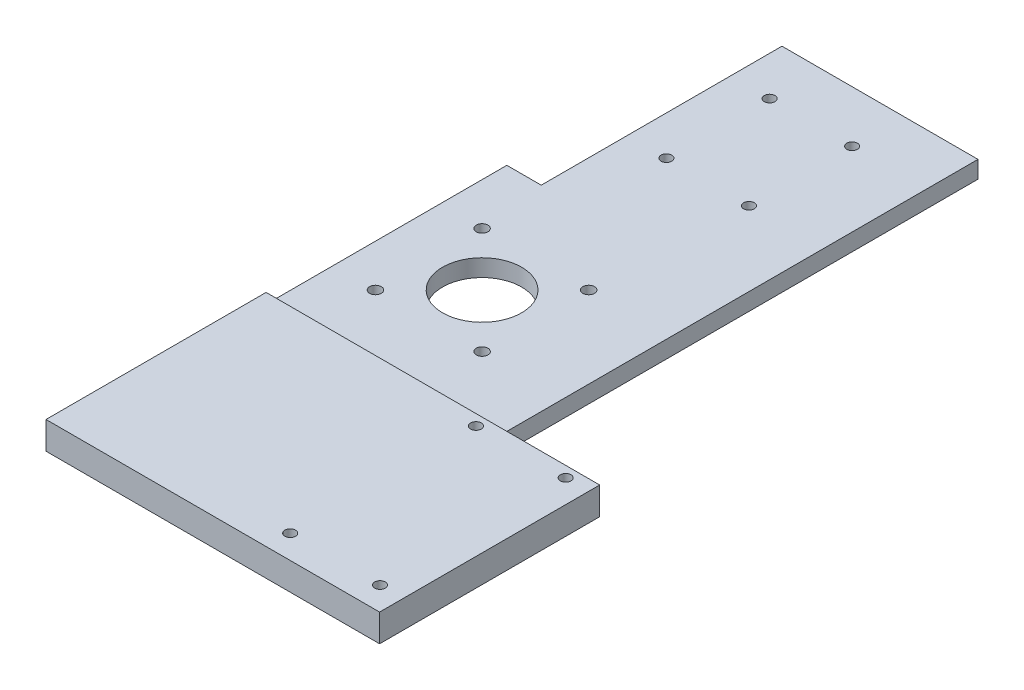
SolidWorks part; units mm, degrees
ref_plane "前视基准面" through (0, 0, 0) normal (0, 0, 1) x (1, 0, 0)
ref_plane "上视基准面" through (0, 0, 0) normal (0, 1, 0) x (1, 0, 0)
ref_plane "右视基准面" through (0, 0, 0) normal (1, 0, 0) x (0, 0, -1)
other "Configuration Table"
sketch "草图1" plane through (0, 0, 0) normal (0, 1, 0) x (1, 0, 0)
  line L1 (0, 0) -> (57, 0)
  line L2 (0, 0) -> (0, -140)
  line L3 (0, -140) -> (57, -140)
  line L4 (57, 0) -> (57, -140)
  dimension "D1" = 57
  dimension "D2" = 140
extrude "凸台-拉伸1" add sketch "草图1" along normal blind 5
sketch "草图2" plane through (0, 0, 0) normal (0, -1, 0) x (1, 0, 0)
  circle A0 centre (11.4, 45) radius 1.55 construction
  circle A1 centre (11.4, 15) radius 1.55 construction
  circle A2 centre (35.4, 15) radius 1.55 construction
  circle A3 centre (35.4, 45) radius 1.55 construction
  circle A4 centre (11.4, 45) radius 1.55
  circle A5 centre (11.4, 15) radius 1.55
  circle A6 centre (35.4, 15) radius 1.55
  circle A7 centre (35.4, 45) radius 1.55
extrude "切除-拉伸1" cut sketch "草图2" against normal blind 10
sketch "草图3" plane through (0, 0, 0) normal (0, -1, 0) x (1, 0, 0)
  line L1 (57, 140) -> (57, 0) construction
  line L2 (0, 140) -> (57, 140) construction
  line L4 (10.5, 89.5) -> (41.5, 89.5) construction
  line L5 (10.5, 89.5) -> (10.5, 120.5) construction
  line L6 (10.5, 120.5) -> (41.5, 120.5) construction
  line L7 (41.5, 89.5) -> (41.5, 120.5) construction
  line L8 (10.5, 89.5) -> (41.5, 120.5) construction
  line L9 (10.5, 120.5) -> (41.5, 89.5) construction
  circle A0 centre (26, 105) radius 32.5 construction
  circle A1 centre (26, 105) radius 11.5
  circle A2 centre (41.5, 120.5) radius 1.7
  circle A3 centre (10.5, 120.5) radius 1.7
  circle A4 centre (10.5, 89.5) radius 1.7
  circle A5 centre (41.5, 89.5) radius 1.7
  dimension "D1" = 65
  dimension "D4" = 23
  dimension "D7" = 3.4
  dimension "D2" = 31
  dimension "D3" = 35
  dimension "D5" = 31
  dimension "D6" = 31
sketch "草图5" plane through (0, 0, 0) normal (-1, 0, 0) x (0, 0, 1)
  line L0 (70, 5) -> (70, 0)
  line L4 (0, 0) -> (140, 0)
  line L5 (140, 0) -> (140, 5)
  line L6 (140, 5) -> (0, 5)
  line L7 (0, 5) -> (0, 0)
  line L8 (70, 0) -> (140, 0)
  line L9 (140, 0) -> (140, 5)
  line L10 (140, 5) -> (70, 5)
  dimension "D2" = 70
  dimension "D1" = 0
extrude "凸台-拉伸2" add sketch "草图5" along normal blind 10
sketch "草图6" plane through (0, 5, 0) normal (0, 1, 0) x (1, 0, 0)
  line L2 (2.3, -120.5) -> (33.3, -120.5) construction
  line L3 (2.3, -120.5) -> (2.3, -89.5) construction
  line L4 (2.3, -89.5) -> (33.3, -89.5) construction
  line L5 (33.3, -120.5) -> (33.3, -89.5) construction
  line L6 (2.3, -120.5) -> (33.3, -89.5) construction
  line L7 (2.3, -89.5) -> (33.3, -120.5) construction
  circle A0 centre (26, -105) radius 11.5 construction
  circle A1 centre (26, -105) radius 11.5 construction
  circle A2 centre (17.8, -105) radius 11.5
  circle A3 centre (33.3, -89.5) radius 1.7
  circle A4 centre (2.3, -89.5) radius 1.7
  circle A5 centre (2.3, -120.5) radius 1.7
  circle A6 centre (33.3, -120.5) radius 1.7
  dimension "D4" = 3.4
  dimension "D1" = 8.2
  dimension "D2" = 31
  dimension "D3" = 31
extrude "切除-拉伸2" cut sketch "草图6" against normal blind 10
sketch "草图7" plane through (0, 5, 0) normal (0, 1, 0) x (1, 0, 0)
  line L0 (57, -140) -> (-10, -140)
  line L1 (-10, -140) -> (-10, -204)
  line L2 (-10, -204) -> (87, -204)
  line L4 (-10, -140) -> (-10, -70) construction
  line L5 (57, -140) -> (87, -140)
  line L6 (87, -140) -> (87, -204.994)
  line M17 (-10, -140) -> (57, -140)
  dimension "D1" = 97
  dimension "D2" = 64
extrude "凸台-拉伸4" add sketch "草图7" against normal blind 5 and the other way blind 3 contours L6 L5 L1 L2 M17
sketch "草图8" plane through (0, 0, 0) normal (0, -1, 0) x (1, 0, 0)
  circle A0 centre (54.15, 197.1379) radius 1.55 construction
  circle A1 centre (80.25, 197.1379) radius 1.55 construction
  circle A2 centre (54.15, 143.1379) radius 1.55 construction
  circle A3 centre (80.25, 143.1379) radius 1.55 construction
  circle A4 centre (54.15, 197.1379) radius 1.55
  circle A5 centre (80.25, 197.1379) radius 1.55
  circle A6 centre (54.15, 143.1379) radius 1.55
  circle A7 centre (80.25, 143.1379) radius 1.55
extrude "切除-拉伸3" cut sketch "草图8" against normal through all both and the other way through all
